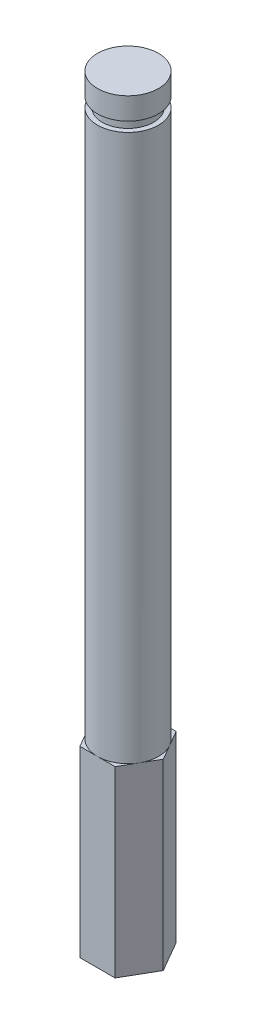
SolidWorks part; units mm, degrees
material "1060 Alloy"
ref_plane "Front Plane" through (0, 0, 0) normal (0, 0, 1) x (1, 0, 0)
ref_plane "Top Plane" through (0, 0, 0) normal (0, 1, 0) x (1, 0, 0)
ref_plane "Right Plane" through (0, 0, 0) normal (1, 0, 0) x (0, 0, -1)
sketch "Sketch1" plane through (0, 0, 0) normal (0, 1, 0) x (1, 0, 0)
  line L1 (1.8331, 3.175) -> (-1.8331, 3.175)
  line L2 (-1.8331, 3.175) -> (-3.6662, 0)
  line L3 (-3.6662, 0) -> (-1.8331, -3.175)
  line L4 (-1.8331, -3.175) -> (1.8331, -3.175)
  line L5 (1.8331, -3.175) -> (3.6662, 0)
  line L6 (3.6662, 0) -> (1.8331, 3.175)
  circle A0 centre (0, 0) radius 3.175 construction
  dimension "D1" = 6.35
extrude "Boss-Extrude1" add sketch "Sketch1" along normal blind 19.05
sketch "Sketch2" plane through (0, 19.05, 0) normal (0, 1, 0) x (1, 0, 0)
  circle A0 centre (0, 0) radius 3.175
extrude "Boss-Extrude2" add sketch "Sketch2" along normal blind 56.896
sketch "Sketch3" plane through (0, 75.946, 0) normal (0, 1, 0) x (1, 0, 0)
  circle A0 centre (0, 0) radius 2.667
  dimension "D1" = 5.334
extrude "Boss-Extrude3" add sketch "Sketch3" along normal blind 1.016
sketch "Sketch4" plane through (0, 76.962, 0) normal (0, 1, 0) x (1, 0, 0)
  circle A0 centre (0, 0) radius 3.175
extrude "Boss-Extrude4" add sketch "Sketch4" along normal blind 2.286
sketch "Sketch5" plane through (0, 0, 0) normal (0, -1, 0) x (1, 0, 0)
  circle A0 centre (0, 0) radius 3.175
